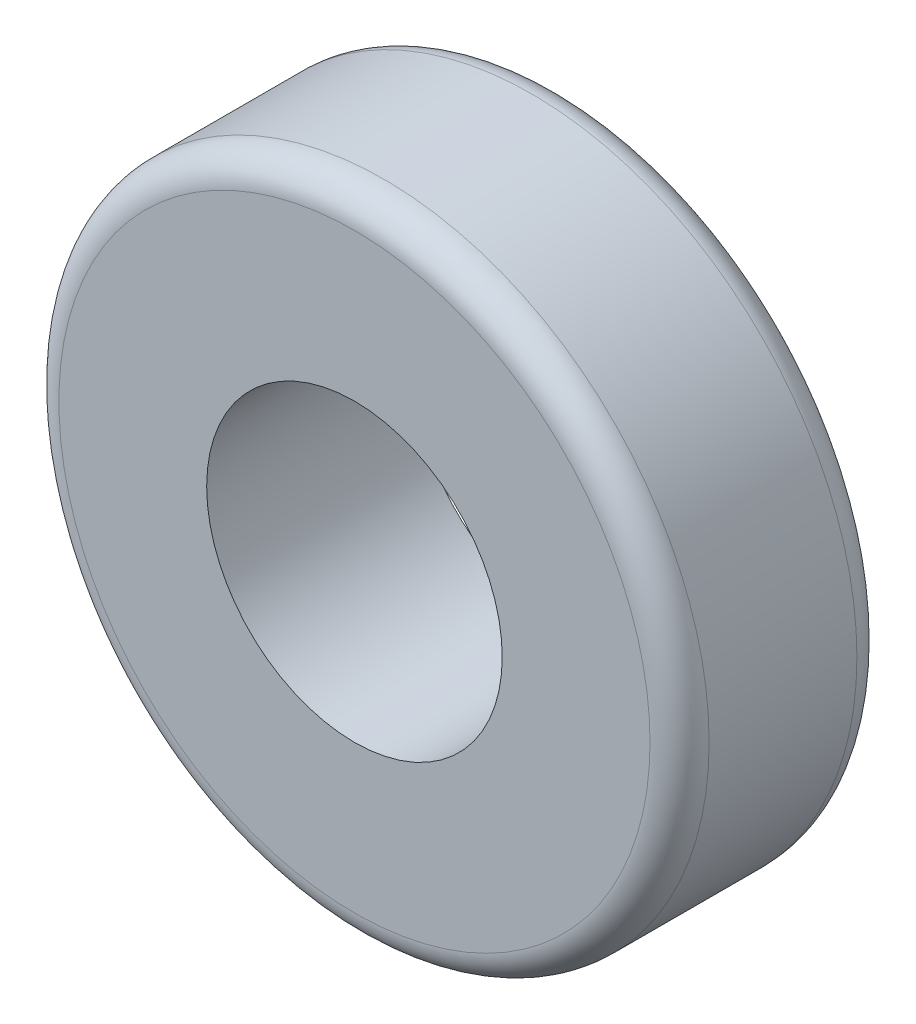
SolidWorks part; units mm, degrees
ref_plane "Alzado" through (0, 0, 0) normal (0, 0, 1) x (1, 0, 0)
ref_plane "Planta" through (0, 0, 0) normal (0, 1, 0) x (1, 0, 0)
ref_plane "Vista lateral" through (0, 0, 0) normal (1, 0, 0) x (0, 0, -1)
sketch "Croquis1" plane through (0, 0, 0) normal (0, 0, 1) x (1, 0, 0)
  circle A0 centre (0, 0) radius 5
  circle A1 centre (0, 0) radius 11
  dimension "D1" = 10
  dimension "D2" = 22
extrude "Saliente-Extruir1" add sketch "Croquis1" along normal blind 7
fillet "Redondeo1" radius 1 2 edges at (11, 0, 0) (11, 0, 7)
